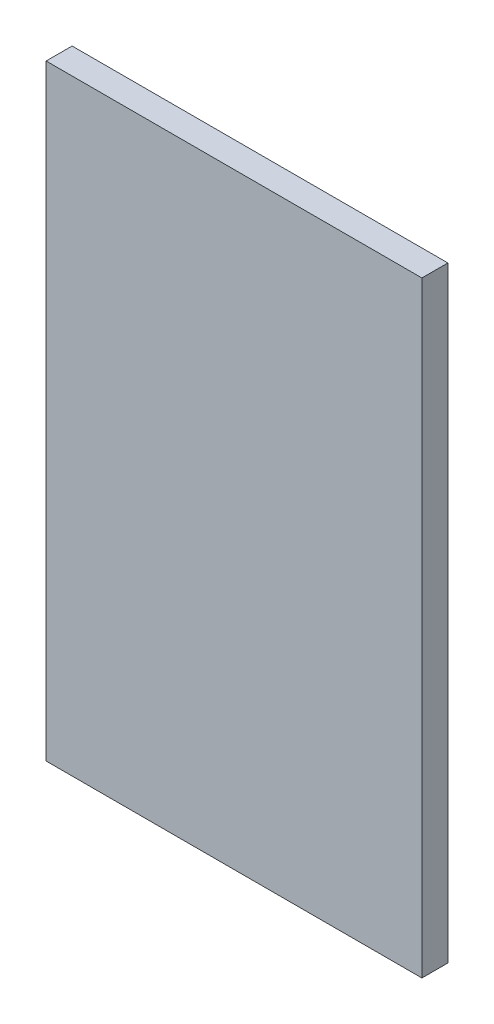
SolidWorks part; units mm, degrees
material "6063-T5"
ref_plane "正面" through (0, 0, 0) normal (0, 0, 1) x (1, 0, 0)
ref_plane "平面" through (0, 0, 0) normal (0, 1, 0) x (1, 0, 0)
ref_plane "右側面" through (0, 0, 0) normal (1, 0, 0) x (0, 0, -1)
sketch "ｽｹｯﾁ1" plane through (0, 0, 0) normal (0, 0, 1) x (1, 0, 0)
  line L1 (21.7, -35.01) -> (-21.7, -35.01)
  line L2 (21.7, -35.01) -> (21.7, 35.01)
  line L3 (21.7, 35.01) -> (-21.7, 35.01)
  line L4 (-21.7, -35.01) -> (-21.7, 35.01)
  line L5 (21.7, -35.01) -> (-21.7, 35.01) construction
  line L6 (21.7, 35.01) -> (-21.7, -35.01) construction
  point P0 (0, 0)
  dimension "D1" = 43.4
  dimension "D2" = 70.02
extrude "ﾎﾞｽ - 押し出し1" add sketch "ｽｹｯﾁ1" along normal blind 3
